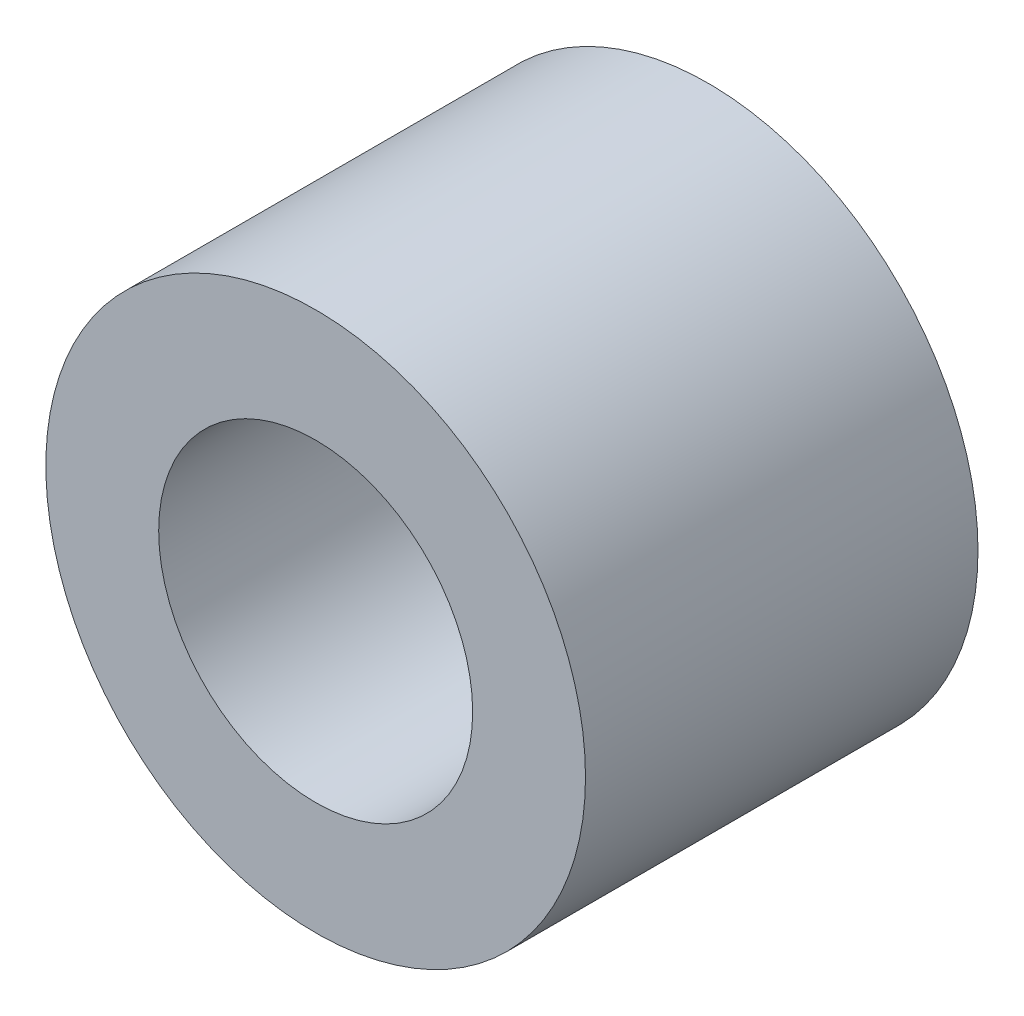
SolidWorks part; units mm, degrees
material "ABS"
ref_plane "Front Plane" through (0, 0, 0) normal (0, 0, 1) x (1, 0, 0)
ref_plane "Top Plane" through (0, 0, 0) normal (0, 1, 0) x (1, 0, 0)
ref_plane "Right Plane" through (0, 0, 0) normal (1, 0, 0) x (0, 0, -1)
sketch "Sketch1" plane through (0, 0, 0) normal (0, 0, 1) x (1, 0, 0)
  circle A0 centre (0, 0) radius 2.75
  circle A1 centre (0, 0) radius 1.6
  dimension "D1" = 5.5
  dimension "D2" = 3.2
extrude "Boss-Extrude1" add sketch "Sketch1" along normal blind 4
